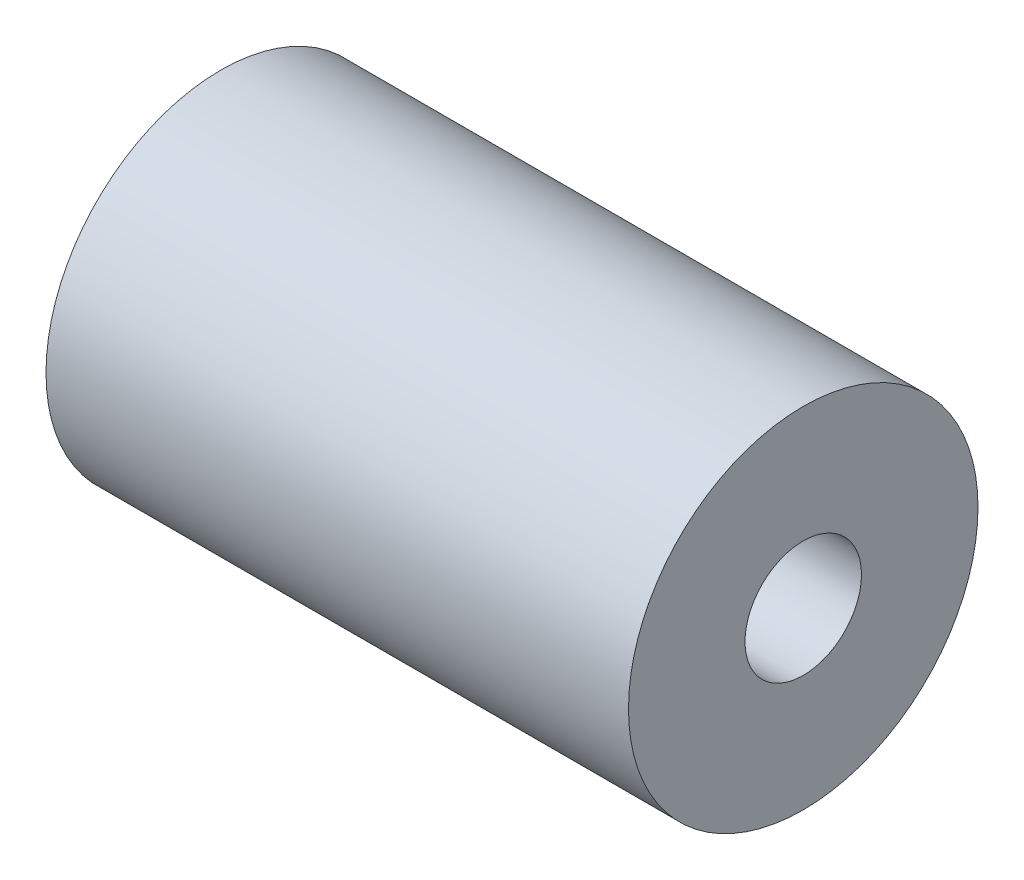
SolidWorks part; units mm, degrees
ref_plane "前视基准面" through (0, 0, 0) normal (0, 0, 1) x (1, 0, 0)
ref_plane "上视基准面" through (0, 0, 0) normal (0, 1, 0) x (1, 0, 0)
ref_plane "右视基准面" through (0, 0, 0) normal (1, 0, 0) x (0, 0, -1)
other "Configuration Table"
sketch "草图1" plane through (0, 0, 0) normal (1, 0, 0) x (0, 0, -1)
  circle A0 centre (0, 0) radius 3
  circle A1 centre (0, 0) radius 1
  dimension "D1" = 6
  dimension "D2" = 2
extrude "凸台-拉伸1" add sketch "草图1" along normal blind 10 contours A0 | A1
